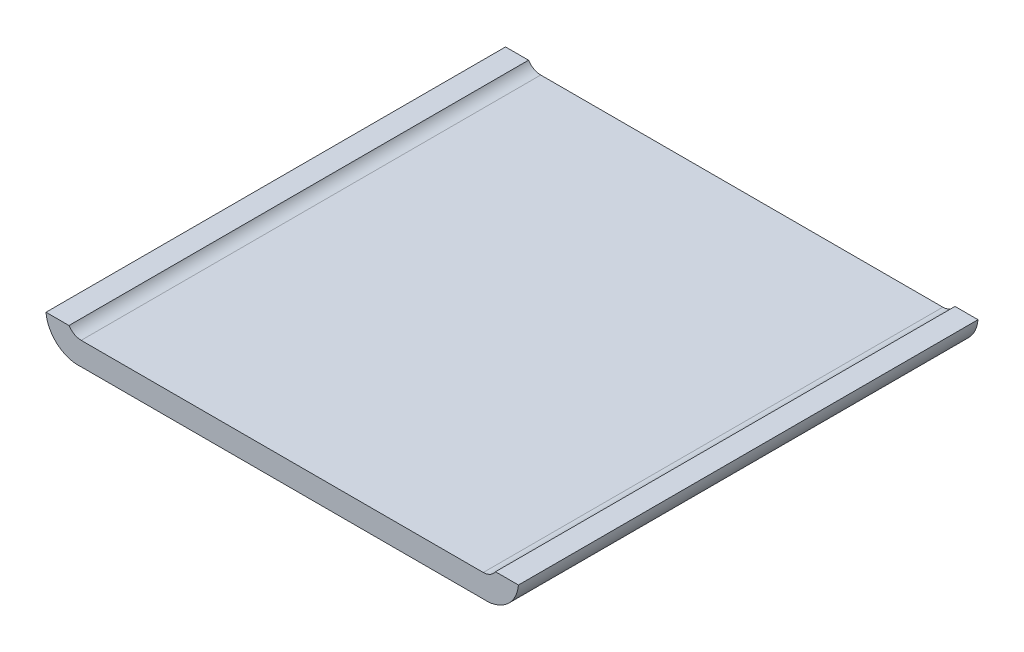
SolidWorks part; units mm, degrees
ref_plane "Front Plane" through (0, 0, 0) normal (0, 0, 1) x (1, 0, 0)
ref_plane "Top Plane" through (0, 0, 0) normal (0, 1, 0) x (1, 0, 0)
ref_plane "Right Plane" through (0, 0, 0) normal (1, 0, 0) x (0, 0, -1)
sketch "Sketch1" plane through (0, 0, 0) normal (0, 0, 1) x (1, 0, 0)
  line L1 (-175, -10) -> (175, -10)
  line L2 (-175, -10) -> (-175, 10)
  line L3 (-175, 10) -> (175, 10)
  line L4 (175, -10) -> (175, 10)
  line L5 (-175, -10) -> (175, 10) construction
  line L6 (-175, 10) -> (175, -10) construction
  point P0 (0, 0)
  dimension "D1" = 350
  dimension "D2" = 20
extrude "Boss-Extrude1" add sketch "Sketch1" along normal blind 400
sketch "Sketch2" plane through (0, 0, 0) normal (0, 0, 1) x (1, 0, 0)
  line L0 (-175, 10) -> (-175, -10)
  line L1 (175, 10) -> (175, -10)
  line L2 (-205.6143, 15.8755) -> (-185.6143, 15.8755)
  arc A0 (-185.6143, 15.8755) -> (-175, 10) centre (-174.8017, 22.8836) ccw
  arc A1 (-205.6143, 15.8755) -> (-175, -10) centre (-177.3694, 18.2449) ccw
  dimension "D1" = 20
extrude "Boss-Extrude2" add sketch "Sketch2" along normal blind 400 contours A0 L0 A1 L2
mirror "Mirror1" about plane through (0, 0, 0) normal (1, 0, 0) of "Boss-Extrude2"
